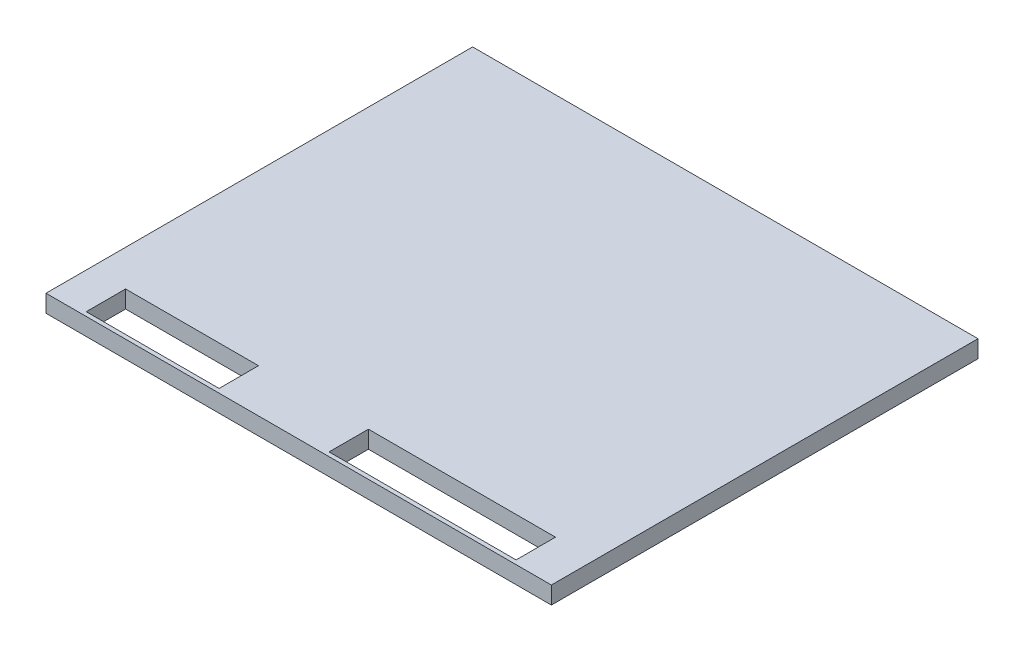
SolidWorks part; units mm, degrees
ref_plane "前视基准面" through (0, 0, 0) normal (0, 0, 1) x (1, 0, 0)
ref_plane "上视基准面" through (0, 0, 0) normal (0, 1, 0) x (1, 0, 0)
ref_plane "右视基准面" through (0, 0, 0) normal (1, 0, 0) x (0, 0, -1)
sketch "草图1" plane through (0, 0, 0) normal (0, 1, 0) x (1, 0, 0)
  line L1 (-102.5558, 114.2155) -> (205.4442, 114.2155)
  line L2 (-102.5558, 114.2155) -> (-102.5558, -145.7845)
  line L3 (-102.5558, -145.7845) -> (205.4442, -145.7845)
  line L4 (205.4442, 114.2155) -> (205.4442, -145.7845)
  dimension "D1" = 308
  dimension "D2" = 260
extrude "凸台-拉伸1" add sketch "草图1" along normal blind 10.6
sketch "草图2" plane through (0, 0, 0) normal (0, 1, 0) x (1, 0, 0)
  line L0 (-102.5558, -145.7845) -> (205.4442, -145.7845) construction
  line L1 (67.4442, -119.2845) -> (181.4442, -119.2845)
  line L2 (67.4442, -119.2845) -> (67.4442, -143.2845)
  line L3 (67.4442, -143.2845) -> (181.4442, -143.2845)
  line L4 (181.4442, -119.2845) -> (181.4442, -143.2845)
  line L5 (205.4442, -145.7845) -> (205.4442, 114.2155) construction
  line L6 (-102.5558, 114.2155) -> (-102.5558, -145.7845) construction
  line L7 (-80.5558, -119.2845) -> (0.4442, -119.2845)
  line L8 (-80.5558, -119.2845) -> (-80.5558, -143.2845)
  line L9 (-80.5558, -143.2845) -> (0.4442, -143.2845)
  line L10 (0.4442, -119.2845) -> (0.4442, -143.2845)
  dimension "D1" = 2.5
  dimension "D2" = 24
  dimension "D3" = 114
  dimension "D4" = 24
  dimension "D5" = 81
  dimension "D6" = 22
  dimension "D7" = 2.5
  dimension "D8" = 24
extrude "切除-拉伸1" cut sketch "草图2" along normal blind 10.6
